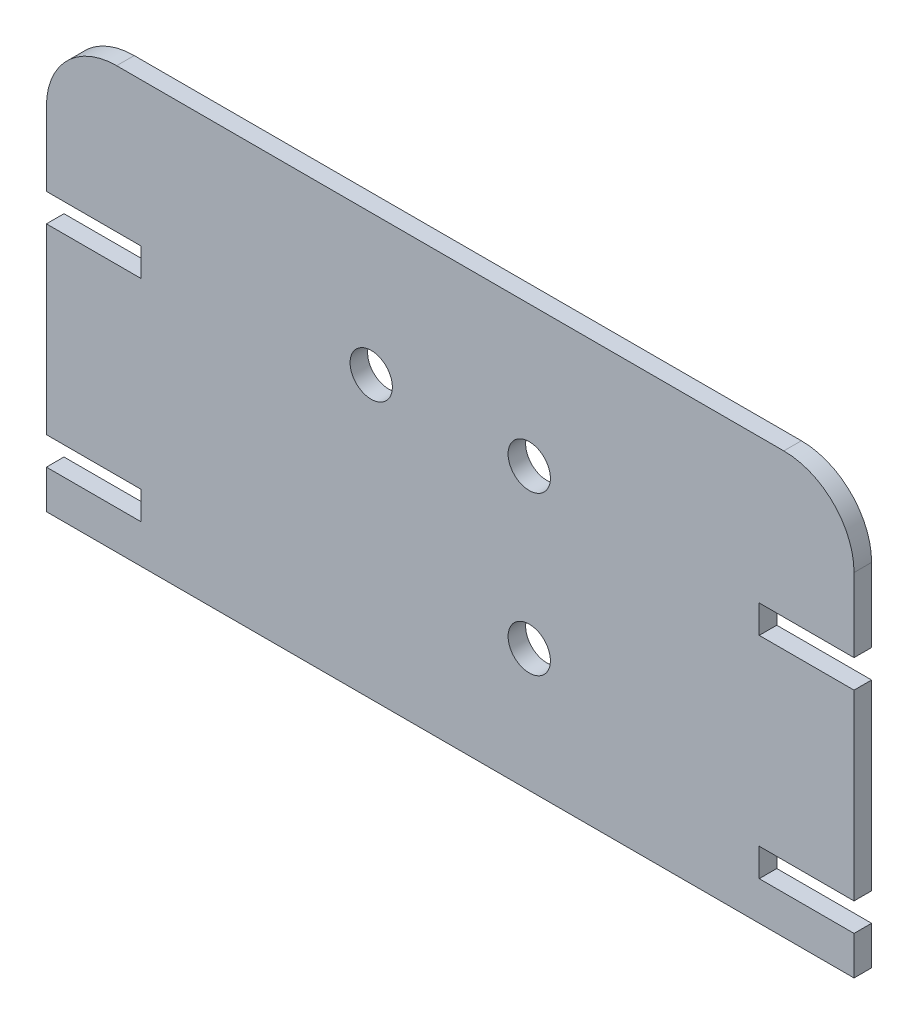
SolidWorks part; units mm, degrees
ref_plane "Front Plane" through (0, 0, 0) normal (0, 0, 1) x (1, 0, 0)
ref_plane "Top Plane" through (0, 0, 0) normal (0, 1, 0) x (1, 0, 0)
ref_plane "Right Plane" through (0, 0, 0) normal (1, 0, 0) x (0, 0, -1)
sketch "Sketch1" plane through (0, 0, 0) normal (0, 0, 1) x (1, 0, 0)
  line L1 (-115, -60) -> (115, -60)
  line L2 (-115, -60) -> (-115, 60)
  line L3 (-115, 60) -> (115, 60)
  line L4 (115, -60) -> (115, 60)
  line L5 (-115, -60) -> (115, 60) construction
  line L6 (-115, 60) -> (115, -60) construction
  point P0 (0, 0)
  dimension "D1" = 230
  dimension "D2" = 120
extrude "Boss-Extrude1" add sketch "Sketch1" along normal blind 5
sketch "Sketch2" plane through (0, 0, 0) normal (0, 0, -1) x (-1, 0, 0)
  line L0 (115, 11) -> (88, 11)
  line L1 (115, 60) -> (115, -60) construction
  line L2 (88, 11) -> (88, 19)
  line L3 (88, 19) -> (115, 19)
  line L4 (115, 19) -> (115, 11)
  line L5 (117.8, 19) -> (115.5, 19) construction
  line L6 (115.5, 11) -> (117.8, 11) construction
  line L7 (115, -49) -> (88, -49)
  line L8 (88, -41) -> (115, -41)
  line L9 (88, -49) -> (88, -41)
  line L10 (115, -41) -> (115, -49)
  line L11 (115.5, -49) -> (117.8, -49) construction
  line L12 (117.8, -41) -> (115.5, -41) construction
  line L13 (115, -40.5) -> (115, -30.5) construction
  line L14 (0, 2.75) -> (0, -2.75) construction
  line L15 (-115, -41) -> (-115, -49)
  line L16 (-88, -49) -> (-88, -41)
  line L17 (-88, -41) -> (-115, -41)
  line L18 (-115, -49) -> (-88, -49)
  line L19 (-115, 19) -> (-115, 11)
  line L20 (-88, 19) -> (-115, 19)
  line L21 (-88, 11) -> (-88, 19)
  line L22 (-115, 11) -> (-88, 11)
  dimension "D1" = 27
  dimension "D2" = 27
extrude "Cut-Extrude1" cut sketch "Sketch2" against normal up to next
sketch "Sketch3" plane through (0, 0, 5) normal (0, 0, 1) x (1, 0, 0)
  line L0 (-115, 20) -> (115, 20) construction
  line L1 (-115, 60) -> (-115, 19) construction
  line L2 (115, 19) -> (115, 60) construction
  line L3 (115, 60) -> (-115, 60) construction
  line L4 (22.5, 60) -> (22.5, -60) construction
  line L5 (-115, -60) -> (115, -60) construction
  circle A0 centre (22.5, 20) radius 6.025
  circle A1 centre (-22.5, 20) radius 6.025
  circle A2 centre (22.5, -25) radius 6.025
  dimension "D2" = 12.05
  dimension "D3" = 45
  dimension "D1" = 40
  dimension "D4" = 45
  dimension "D5" = 22.5
extrude "Cut-Extrude2" cut sketch "Sketch3" against normal up to next
fillet "Fillet1" radius 20 2 edges at (115, 60, 2.5) (-115, 60, 2.5)
